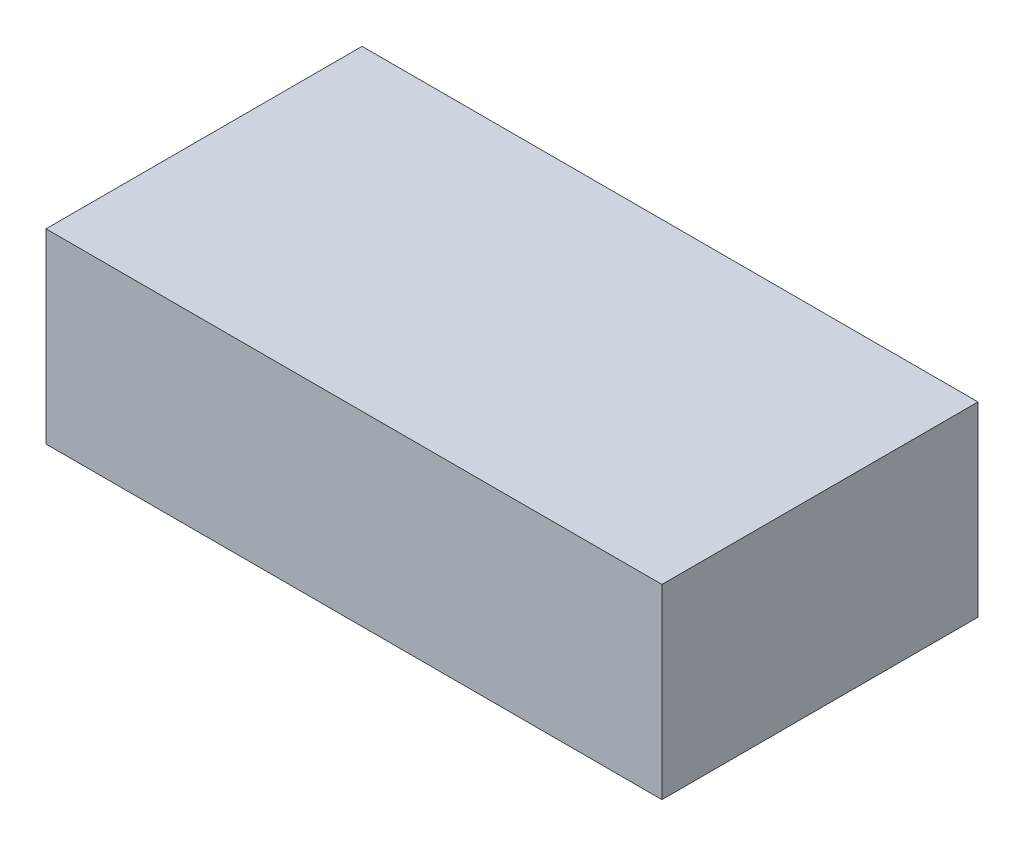
SolidWorks part; units mm, degrees
ref_plane "Front Plane" through (0, 0, 0) normal (0, 0, 1) x (1, 0, 0)
ref_plane "Top Plane" through (0, 0, 0) normal (0, 1, 0) x (1, 0, 0)
ref_plane "Right Plane" through (0, 0, 0) normal (1, 0, 0) x (0, 0, -1)
sketch "Sketch1" plane through (0, 0, 0) normal (0, 1, 0) x (1, 0, 0)
  line L1 (0, 0) -> (76, 0)
  line L2 (0, 0) -> (0, -39)
  line L3 (0, -39) -> (76, -39)
  line L4 (76, 0) -> (76, -39)
  dimension "D1" = 76
  dimension "D2" = 39
extrude "Boss-Extrude1" add sketch "Sketch1" along normal blind 23
